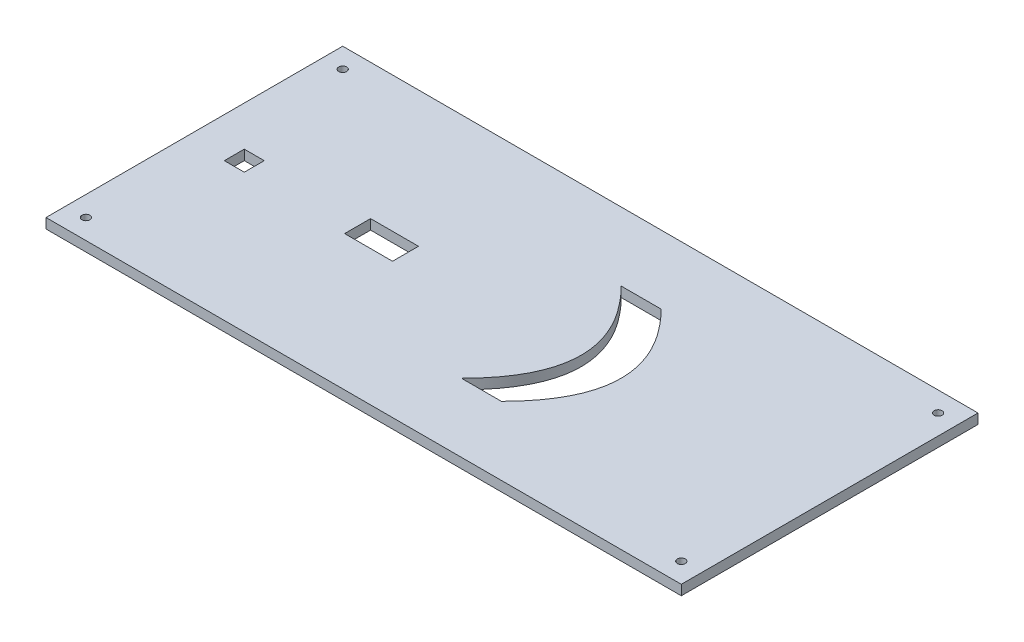
SolidWorks part; units mm, degrees
material "PMMA"
ref_plane "Plan de face" through (0, 0, 0) normal (0, 0, 1) x (1, 0, 0)
ref_plane "Plan de dessus" through (0, 0, 0) normal (0, 1, 0) x (1, 0, 0)
ref_plane "Plan de droite" through (0, 0, 0) normal (1, 0, 0) x (0, 0, -1)
sketch "Esquisse2" plane through (0, 0, 0) normal (0, 1, 0) x (1, 0, 0)
  line L0 (-31.7655, -2.8878) -> (286.3845, -2.8878)
  line L2 (-31.7655, -2.8878) -> (286.3845, -2.8878)
  line L3 (-31.7655, -2.8878) -> (-31.7655, -151.4778)
  line L4 (-31.7655, -151.4778) -> (286.3845, -151.4778)
  line L5 (286.3845, -2.8878) -> (286.3845, -151.4778)
extrude "Boss.-Extru.1" add sketch "Esquisse2" along normal blind 5 contours L5 L0 L3 L4
sketch "Esquisse3" plane through (0, 5, 0) normal (0, 1, 0) x (1, 0, 0)
  line L0 (-31.7655, -151.4778) -> (-31.7655, -141.4778)
  line L1 (-31.7655, -2.8878) -> (-31.7655, -151.4778) construction
  line L2 (-31.7655, -141.4778) -> (-21.7655, -141.4778)
  line L3 (-31.7655, -2.8878) -> (-21.7655, -2.8878)
  line L4 (-31.7655, -2.8878) -> (286.3845, -2.8878) construction
  line L5 (-21.7655, -2.8878) -> (-21.7655, -12.8878)
  line L6 (286.3845, -2.8878) -> (286.3845, -12.8878)
  line L7 (286.3845, -2.8878) -> (286.3845, -151.4778) construction
  line L8 (286.3845, -12.8878) -> (276.3845, -12.8878)
  line L9 (286.3845, -151.4778) -> (276.3845, -151.4778)
  line L10 (-31.7655, -151.4778) -> (286.3845, -151.4778) construction
  line L11 (276.3845, -151.4778) -> (276.3845, -141.4778)
  circle A0 centre (276.3845, -141.4778) radius 2
  circle A1 centre (276.3845, -12.8878) radius 2
  circle A2 centre (-21.7655, -12.8878) radius 2
  circle A3 centre (-21.7655, -141.4778) radius 2
extrude "Enlèv. mat.-Extru.1" cut sketch "Esquisse3" against normal blind 5
sketch "Esquisse4" plane through (0, 5, 0) normal (0, 1, 0) x (1, 0, 0)
  line L0 (286.3845, -151.4778) -> (286.3845, -2.8878)
  line L1 (286.3845, -2.8878) -> (286.3845, -77.1828)
  line L2 (286.3845, -77.1828) -> (56.9825, -77.1828)
  line L3 (56.9825, -77.1828) -> (49.9825, -77.1828)
  line L4 (49.9825, -77.1828) -> (49.9825, -70.6828)
  line L5 (49.9825, -77.1828) -> (49.9825, -83.6828)
  line L6 (49.9825, -83.6828) -> (73.9825, -83.6828)
  line L7 (73.9825, -83.6828) -> (73.9825, -70.6828)
  line L8 (73.9825, -70.6828) -> (49.9825, -70.6828)
extrude "Enlèv. mat.-Extru.2" cut sketch "Esquisse4" against normal blind 5 contours L6 L7 L2 L3 L5 | L7 L8 L4 L3 L2
sketch "Esquisse6" plane through (0, 0, 0) normal (0, -1, 0) x (-1, 0, 0)
  line L8 (-161.9825, -37.1828) -> (-141.9825, -37.1828)
  line L9 (-161.9825, -117.1828) -> (-141.9825, -117.1828)
  spline S0 degree 2 poles (-141.9825, -117.1828) (-181.9825, -77.1828) (-141.9825, -37.1828) knots 0 0 0 1 1 1
  spline S1 degree 2 poles (-161.9825, -117.1828) (-201.9825, -77.1828) (-161.9825, -37.1828) knots 0 0 0 1 1 1
extrude "Enlèv. mat.-Extru.3" cut sketch "Esquisse6" against normal blind 5 contours L9 S0 L8 S1
sketch "Esquisse7" plane through (0, 0, 0) normal (0, -1, 0) x (-1, 0, 0)
  line L0 (31.7655, -151.4778) -> (31.7655, -77.1828)
  line L1 (31.7655, -2.8878) -> (31.7655, -151.4778) construction
  line L2 (11.7655, -72.1828) -> (11.7655, -82.1828)
  line L5 (1.7655, -72.1828) -> (11.7655, -72.1828)
  line L6 (11.7655, -82.1828) -> (1.7655, -82.1828)
  line L7 (1.7655, -72.1828) -> (1.7655, -82.1828)
extrude "Enlèv. mat.-Extru.4" cut sketch "Esquisse7" against normal blind 5 contours L5 L7 L6 L2
